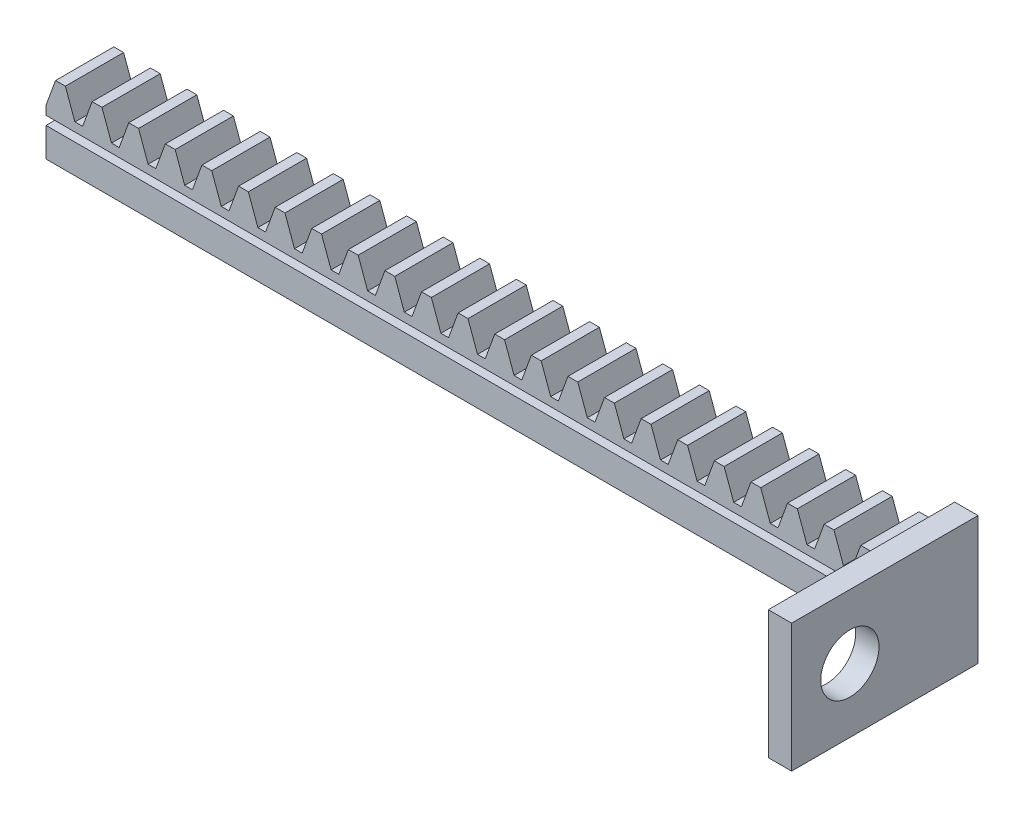
SolidWorks part; units mm, degrees
ref_plane "前视基准面" through (0, 0, 0) normal (0, 0, 1) x (1, 0, 0)
ref_plane "上视基准面" through (0, 0, 0) normal (0, 1, 0) x (1, 0, 0)
ref_plane "右视基准面" through (0, 0, 0) normal (1, 0, 0) x (0, 0, -1)
sketch "草图1" plane through (0, 0, 0) normal (0, 0, 1) x (1, 0, 0)
  line L1 (0, 0) -> (150, 0)
  line L2 (0, 0) -> (0, -8)
  line L3 (0, -8) -> (150, -8)
  line L4 (150, 0) -> (150, -8)
  dimension "D1" = 8
  dimension "L" = 150
extrude "拉伸1" add sketch "草图1" along normal blind 10
sketch "草图2" plane through (0, 0, 10) normal (0, 0, 1) x (1, 0, 0)
  line L0 (0, 0) -> (1.6379, 4.5)
  line L1 (1.6379, 4.5) -> (3.3236, 4.5)
  line L2 (3.3236, 4.5) -> (4.9614, 0)
  line L3 (150, 0) -> (0, 0) construction
  line L4 (0, 0) -> (4.9614, 0)
  line L5 (0.9099, 2.5) -> (4.0515, 2.5) construction
  dimension "D2" = 70
  dimension "alpha" = 110
  dimension "ha" = 2
  dimension "hf" = 2.5
  dimension "S" = 3.1416
extrude "拉伸2" add sketch "草图2" against normal up to surface (10 mm away) up to face at (75, -4, 0)
pattern_linear "阵列(线性)1" count 24 spacing 6.2832 along (1, 0, 0) of "拉伸2"
sketch "草图3" plane through (0, 0, 0) normal (-1, 0, 0) x (0, 0, 1)
  line L0 (10, 0) -> (10, -8) construction
  line L1 (10, -1.5) -> (8, -1.5)
  line L2 (10, -1.5) -> (10, -3)
  line L3 (10, -3) -> (8, -3)
  line L4 (8, -1.5) -> (8, -3)
  line L5 (10, -8) -> (0, -8) construction
  line L6 (0, -6) -> (2, -6)
  line L7 (0, -6) -> (0, -4.5)
  line L8 (0, -4.5) -> (2, -4.5)
  line L9 (2, -6) -> (2, -4.5)
  line L10 (0, 0) -> (0, -8) construction
  dimension "D1" = 1.5
  dimension "D2" = 1.5
  dimension "D3" = 2
  dimension "D4" = 2
  dimension "D5" = 5
  dimension "D6" = 2
extrude "切除-拉伸1" cut sketch "草图3" against normal through all
sketch "草图4" plane through (150, 0, 0) normal (1, 0, 0) x (0, 0, -1)
  line L0 (0, 4.5) -> (0, 0) construction
  line L1 (0, 9) -> (-32, 9)
  line L2 (0, 9) -> (0, -13)
  line L3 (0, -13) -> (-32, -13)
  line L4 (-32, 9) -> (-32, -13)
  line L5 (-10, -8) -> (0, -8) construction
  circle A0 centre (-22, -2) radius 5
  dimension "D1" = 10
  dimension "D4" = 5
  dimension "D2" = 22
  dimension "D3" = 32
  dimension "D5" = 10
  dimension "D6" = 11
extrude "凸台-拉伸1" add sketch "草图4" against normal blind 4
sketch "草图5" plane through (0, 0, 0) normal (0, 0, -1) x (-1, 0, 0)
equation "\"d\"=\"S@草图2\" * 2"
equation "\"z\"= int(  \"L@草图1\" / (  \"S@草图2\" * 2 ) + 0.5 )"
